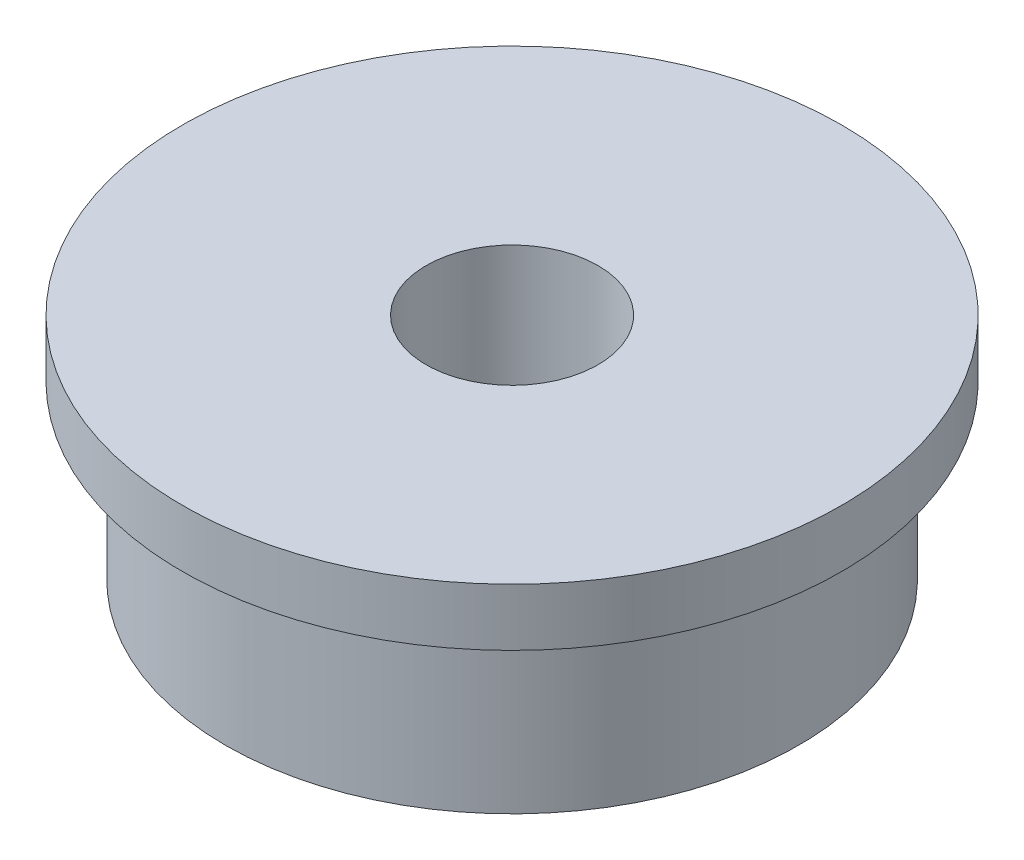
SolidWorks part; units mm, degrees
ref_plane "前视基准面" through (0, 0, 0) normal (0, 0, 1) x (1, 0, 0)
ref_plane "上视基准面" through (0, 0, 0) normal (0, 1, 0) x (1, 0, 0)
ref_plane "右视基准面" through (0, 0, 0) normal (1, 0, 0) x (0, 0, -1)
other "Configuration Table"
sketch "草图1" plane through (0, 0, 0) normal (0, 0, 1) x (1, 0, 0)
  line L0 (0, 0) -> (0, 5.5663) construction
  line L1 (1.5, 0) -> (1.5, 4)
  line L2 (1.5, 4) -> (5.75, 4)
  line L3 (5.75, 4) -> (5.75, 3)
  line L4 (5.75, 3) -> (5, 3)
  line L5 (5, 3) -> (5, 0)
  line L6 (5, 0) -> (1.5, 0)
  dimension "D1" = 11.5
  dimension "D2" = 1
  dimension "D3" = 3
  dimension "D4" = 3
  dimension "D5" = 10
revolve "旋转1" add sketch "草图1" angle 360 about L0
